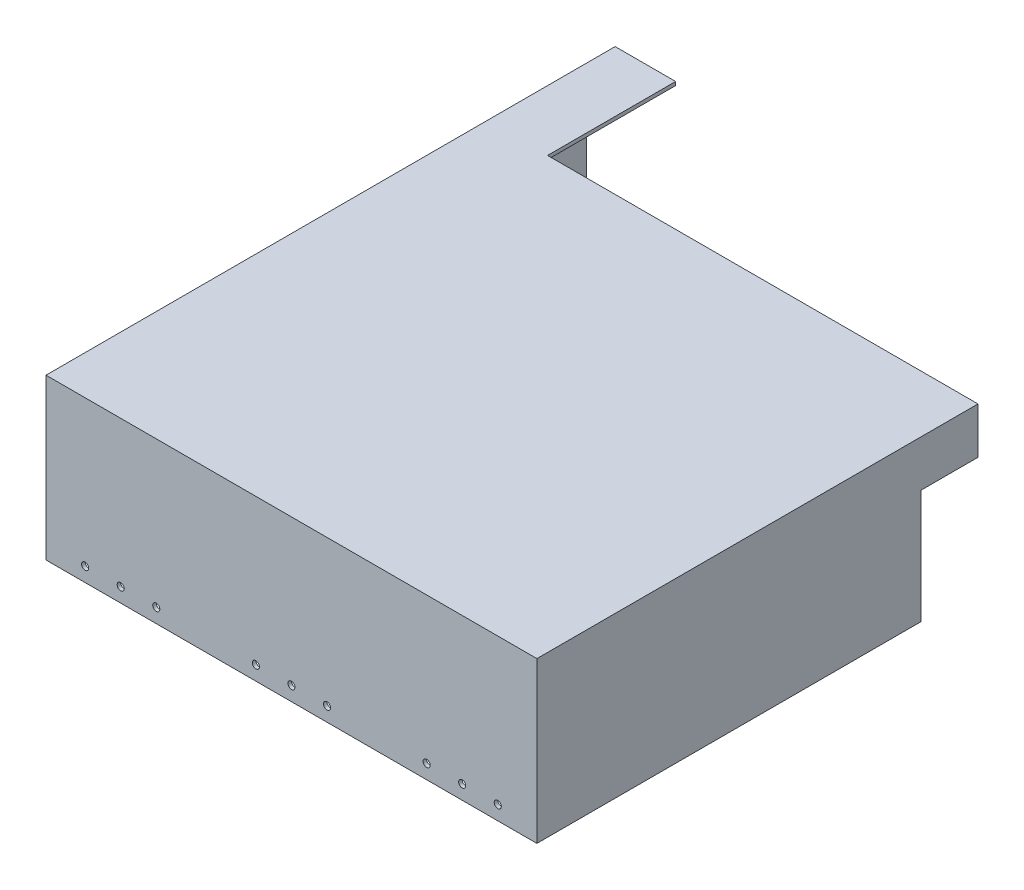
SolidWorks part; units mm, degrees
ref_plane "Front Plane" through (0, 0, 0) normal (0, 0, 1) x (1, 0, 0)
ref_plane "Top Plane" through (0, 0, 0) normal (0, 1, 0) x (1, 0, 0)
ref_plane "Right Plane" through (0, 0, 0) normal (1, 0, 0) x (0, 0, -1)
sketch "Sketch1" plane through (0, 0, 0) normal (0, 0, 1) x (1, 0, 0)
  line L0 (0, 0) -> (3.175, 0)
  line L1 (3.175, 0) -> (3.175, 139.7)
  line L2 (3.175, 139.7) -> (434.975, 139.7)
  line L3 (434.975, 139.7) -> (434.975, 0)
  line L4 (434.975, 0) -> (438.15, 0)
  line L5 (438.15, 0) -> (438.15, 142.875)
  line L6 (438.15, 142.875) -> (0, 142.875)
  line L7 (0, 142.875) -> (0, 0)
  line L8 (3.175, 139.7) -> (3.175, 142.875) construction
  dimension "D1" = 139.7
  dimension "D2" = 431.8
  dimension "D3" = 3.175
extrude "Boss-Extrude1" add sketch "Sketch1" along normal blind 508
sketch "Sketch2" plane through (0, 0, 508) normal (0, 0, 1) x (1, 0, 0)
  line L1 (0, 142.875) -> (438.15, 142.875)
  line L2 (0, 142.875) -> (0, 0)
  line L3 (0, 0) -> (438.15, 0)
  line L4 (438.15, 142.875) -> (438.15, 0)
extrude "Boss-Extrude2" add sketch "Sketch2" against normal blind 3.175
sketch "Sketch4" plane through (0, 142.875, 0) normal (0, 1, 0) x (1, 0, 0)
  line L0 (438.15, 0) -> (0, 0) construction
  line L1 (53.975, 0) -> (438.15, 0)
  line L2 (53.975, 0) -> (53.975, -114.3)
  line L3 (53.975, -114.3) -> (438.15, -114.3)
  line L4 (438.15, 0) -> (438.15, -114.3)
  line L5 (438.15, -508) -> (438.15, 0) construction
  line L6 (0, -508) -> (0, 0) construction
  dimension "D1" = 114.3
  dimension "D2" = 53.975
extrude "Cut-Extrude1" cut sketch "Sketch4" against normal through all
sketch "Sketch5" plane through (438.15, 0, 0) normal (1, 0, 0) x (0, 0, -1)
  line L1 (-114.3, 0) -> (-165.1, 0)
  line L2 (-114.3, 0) -> (-114.3, 101.6)
  line L3 (-114.3, 101.6) -> (-165.1, 101.6)
  line L4 (-165.1, 0) -> (-165.1, 101.6)
  dimension "D1" = 50.8
  dimension "D2" = 101.6
extrude "Cut-Extrude2" cut sketch "Sketch5" against normal up to next
sketch "Sketch6" plane through (0, 0, 0) normal (-1, 0, 0) x (0, 0, 1)
  line L0 (508, 142.875) -> (0, 142.875) construction
  line L1 (0, 0) -> (28.575, 0)
  line L2 (0, 0) -> (0, 117.475)
  line L3 (0, 117.475) -> (28.575, 117.475)
  line L4 (28.575, 0) -> (28.575, 117.475)
  dimension "D1" = 25.4
  dimension "D2" = 28.575
extrude "Cut-Extrude3" cut sketch "Sketch6" against normal up to next
sketch "Sketch7" plane through (0, 0, 508) normal (0, 0, 1) x (1, 0, 0)
  line L0 (219.075, 142.875) -> (219.075, 0) construction
  line L1 (438.15, 142.875) -> (0, 142.875) construction
  line L2 (0, 0) -> (438.15, 0) construction
  circle A0 centre (219.075, 12.7) radius 3.175
  circle A1 centre (187.325, 12.7) radius 3.175
  circle A2 centre (34.925, 12.7) radius 3.175
  circle A3 centre (66.675, 12.7) radius 3.175
  circle A4 centre (98.425, 12.7) radius 3.175
  circle A5 centre (250.825, 12.7) radius 3.175
  circle A6 centre (339.725, 12.7) radius 3.175
  circle A7 centre (371.475, 12.7) radius 3.175
  circle A8 centre (403.225, 12.7) radius 3.175
  point P16 (0, 0)
  point P17 (0, 0)
  dimension "D4" = 6.35
  dimension "D1" = 63.5
  dimension "D2" = 31.75
  dimension "D3" = 63.5
  dimension "D5" = 152.4
  dimension "D6" = 12.7
extrude "Cut-Extrude4" cut sketch "Sketch7" against normal up to surface (3.175 mm away) up to face at (219.075, 69.85, 504.825)
equation "\"D2@Sketch7\"=\"D1@Sketch7\"/2"
